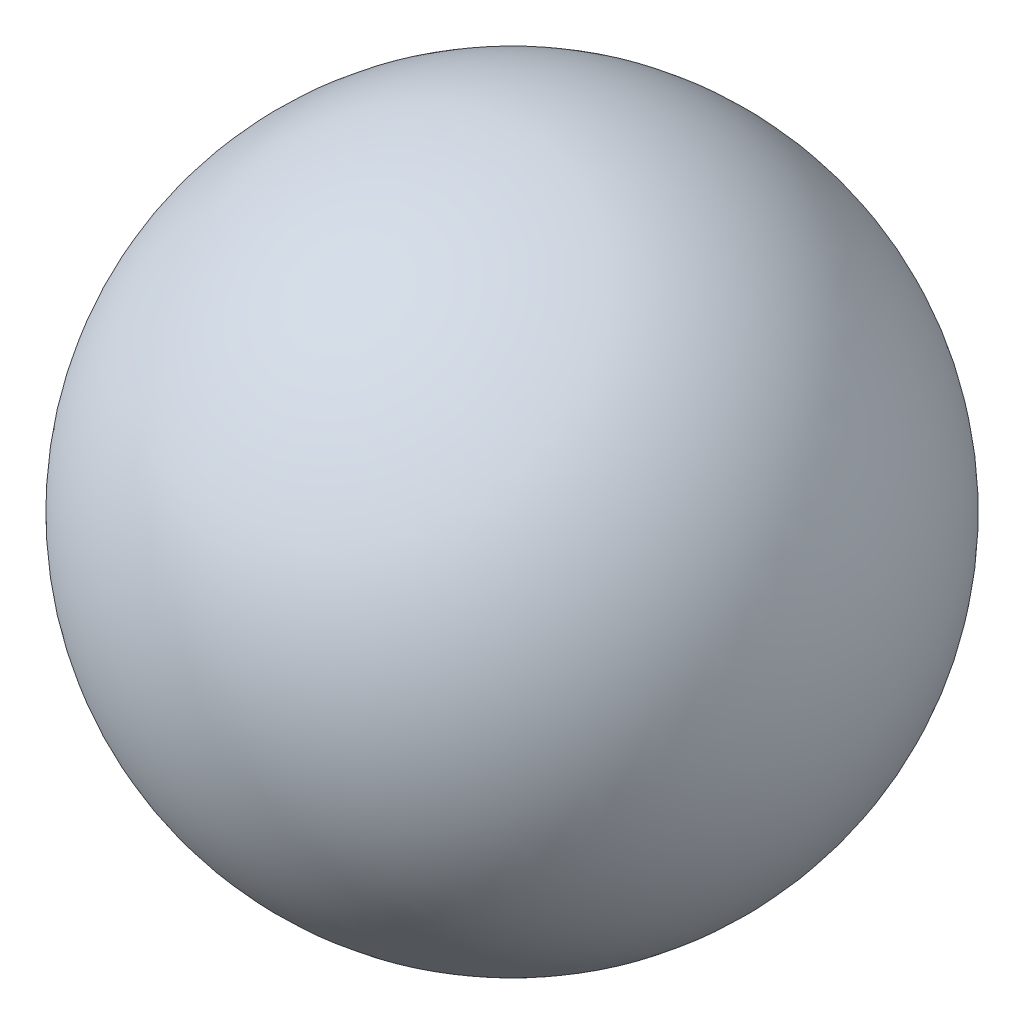
SolidWorks part; units mm, degrees
ref_plane "Alzado" through (0, 0, 0) normal (0, 0, 1) x (1, 0, 0)
ref_plane "Planta" through (0, 0, 0) normal (0, 1, 0) x (1, 0, 0)
ref_plane "Vista lateral" through (0, 0, 0) normal (1, 0, 0) x (0, 0, -1)
sketch "Croquis1" plane through (0, 0, 0) normal (0, 0, 1) x (1, 0, 0)
  line L0 (0, 25.8134) -> (0, -27.2794) construction
  line L2 (0, -21.5) -> (0, 21.5)
  arc A0 (0, -21.5) -> (0, 21.5) centre (0, 0) ccw
  dimension "D1" = 43
revolve "Revolución2" add sketch "Croquis1" angle 360 about L0
